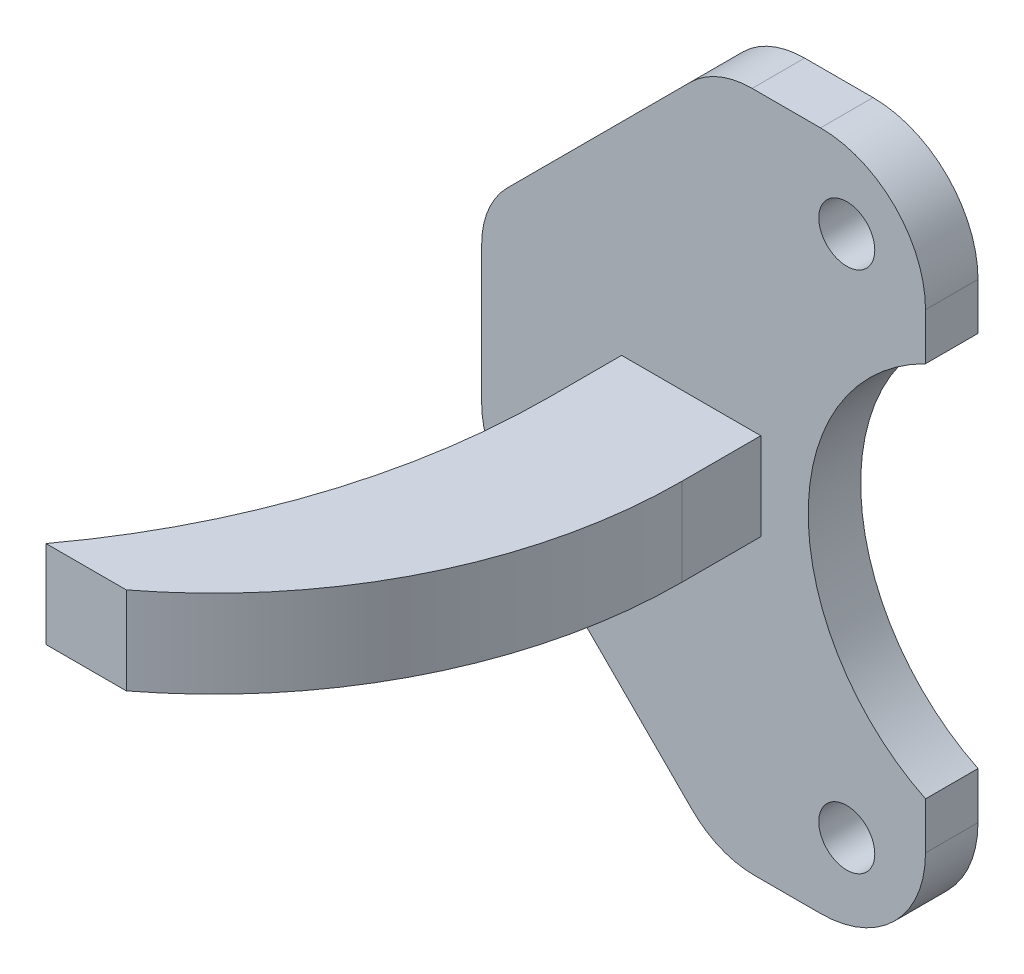
SolidWorks part; units mm, degrees
ref_plane "Front Plane" through (0, 0, 0) normal (0, 0, 1) x (1, 0, 0)
ref_plane "Top Plane" through (0, 0, 0) normal (0, 1, 0) x (1, 0, 0)
ref_plane "Right Plane" through (0, 0, 0) normal (1, 0, 0) x (0, 0, -1)
sketch "Sketch1" plane through (0, 0, 0) normal (0, 0, 1) x (1, 0, 0)
  line L0 (41.5, -10.7682) -> (41.5, -13.4441)
  line L1 (35.5, 19.4441) -> (31.5922, 19.4441)
  line L2 (41.5, 13.4441) -> (41.5, 10.7682)
  line L3 (35.5, -19.4441) -> (31.7037, -19.4441)
  line L5 (28.0567, 17.9796) -> (17.5972, 7.5202)
  line L6 (16.1328, 3.9847) -> (16.1328, -3.8732)
  line L7 (17.5972, -7.4087) -> (28.1681, -17.9796)
  circle A0 centre (37, 14.9441) radius 1.6 construction
  circle A1 centre (37, -14.9441) radius 1.6 construction
  arc A2 (42, 11) -> (42, -11) centre (46.7958, 0) ccw construction
  arc A3 (41.5, 10.7682) -> (41.5, -10.7682) centre (46.7958, 0) ccw
  arc A4 (41.5, -13.4441) -> (35.5, -19.4441) centre (35.5, -13.4441) cw
  arc A5 (35.5, 19.4441) -> (41.5, 13.4441) centre (35.5, 13.4441) cw
  arc A6 (28.0567, 17.9796) -> (31.5922, 19.4441) centre (31.5922, 14.4441) cw
  arc A7 (28.1681, -17.9796) -> (31.7037, -19.4441) centre (31.7037, -14.4441) ccw
  arc A8 (17.5972, 7.5202) -> (16.1328, 3.9847) centre (21.1328, 3.9847) ccw
  arc A9 (16.1328, -3.8732) -> (17.5972, -7.4087) centre (21.1328, -3.8732) ccw
  circle A10 centre (37, 14.9441) radius 1.6
  circle A11 centre (37, -14.9441) radius 1.6
  point P25 (16.1328, 6.0557)
  point P28 (16.1328, -5.9443)
  dimension "D4" = 6
  dimension "D8" = 5
  dimension "D1" = 4.5
  dimension "D2" = 4.5
  dimension "D3" = 4.5
  dimension "D5" = 135
  dimension "D6" = 135
  dimension "D7" = 12
extrude "Boss-Extrude1" add sketch "Sketch1" along normal blind 3
sketch "Sketch2" plane through (0, 0, 0) normal (0, 1, 0) x (1, 0, 0)
  line L0 (32.0858, -3) -> (32.0858, -7.5157)
  line L2 (24.1328, -3) -> (24.1328, -7.1328)
  line L4 (21.5846, -28.7634) -> (16.9968, -28.7634)
  line L5 (24.1328, -3) -> (32.0858, -3)
  line L6 (16.1328, -3) -> (24.1328, -3) construction
  line L7 (28.0567, -3) -> (17.5972, -3) construction
  arc A0 (32.0858, -7.5157) -> (21.5846, -28.7634) centre (5.3394, -7.5157) cw
  arc A1 (24.1328, -7.1328) -> (16.9968, -28.7634) centre (-12.2187, -7.1328) cw
  dimension "D1" = 8
extrude "Boss-Extrude2" add sketch "Sketch2" along normal mid plane 5
